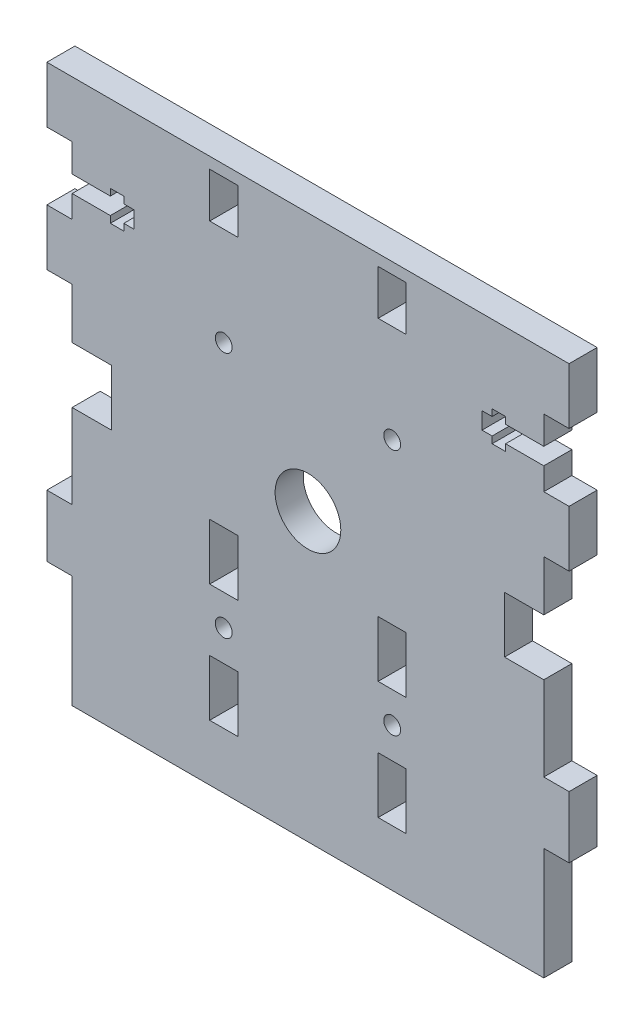
SolidWorks part; units mm, degrees
ref_plane "Plano frontal" through (0, 0, 0) normal (0, 0, 1) x (1, 0, 0)
ref_plane "Plano superior" through (0, 0, 0) normal (0, 1, 0) x (1, 0, 0)
ref_plane "Plano direito" through (0, 0, 0) normal (1, 0, 0) x (0, 0, -1)
sketch "Model" plane through (0, 0, 0) normal (0, 0, 1) x (1, 0, 0)
  line L0 (-56.5, 54) -> (-51.5, 54)
  line L1 (-51.5, 54) -> (-51.5, 64)
  line L2 (-51.5, 64) -> (-56.5, 64)
  line L3 (-56.5, 64) -> (-56.5, 54)
  line L4 (-26.5, 75) -> (-21.5, 75)
  line L5 (-21.5, 75) -> (-21.5, 85)
  line L6 (-21.5, 85) -> (-26.5, 85)
  line L7 (-26.5, 85) -> (-26.5, 75)
  line L8 (-56.5, 131) -> (-51.5, 131)
  line L9 (-51.5, 131) -> (-51.5, 139)
  line L10 (-51.5, 139) -> (-56.5, 139)
  line L11 (-56.5, 139) -> (-56.5, 131)
  line L12 (-26.5, 131) -> (-21.5, 131)
  line L13 (-21.5, 131) -> (-21.5, 139)
  line L14 (-21.5, 139) -> (-26.5, 139)
  line L15 (-26.5, 139) -> (-26.5, 131)
  line L16 (-26.5, 54) -> (-21.5, 54)
  line L17 (-21.5, 54) -> (-21.5, 64)
  line L18 (-21.5, 64) -> (-26.5, 64)
  line L19 (-26.5, 64) -> (-26.5, 54)
  line L20 (-56.5, 75) -> (-51.5, 75)
  line L21 (-51.5, 75) -> (-51.5, 85)
  line L22 (-51.5, 85) -> (-56.5, 85)
  line L23 (-56.5, 85) -> (-56.5, 75)
  line L24 (-85.5, 109) -> (-85.5, 119)
  line L25 (-85.5, 119) -> (-81, 119)
  line L26 (-81, 119) -> (-81, 123)
  line L27 (-81, 123) -> (-74.2, 123)
  line L28 (-74.2, 123) -> (-74.2, 121.8)
  line L29 (-74.2, 121.8) -> (-71.8, 121.8)
  line L30 (-71.8, 121.8) -> (-71.8, 123)
  line L31 (-71.8, 123) -> (-70, 123)
  line L32 (-70, 123) -> (-70, 126)
  line L33 (-70, 126) -> (-71.8, 126)
  line L34 (-71.8, 126) -> (-71.8, 127.2)
  line L35 (-71.8, 127.2) -> (-74.2, 127.2)
  line L36 (-74.2, 127.2) -> (-74.2, 126)
  line L37 (-74.2, 126) -> (-81, 126)
  line L38 (-81, 126) -> (-81, 131)
  line L39 (-81, 131) -> (-85.5, 131)
  line L40 (-85.5, 131) -> (-85.5, 141)
  line L41 (-85.5, 141) -> (7.5, 141)
  line L42 (7.5, 141) -> (7.5, 131)
  line L43 (7.5, 131) -> (3, 131)
  line L44 (3, 131) -> (3, 126)
  line L45 (3, 126) -> (-3.8, 126)
  line L46 (-3.8, 126) -> (-3.8, 127.2)
  line L47 (-3.8, 127.2) -> (-6.2, 127.2)
  line L48 (-6.2, 127.2) -> (-6.2, 126)
  line L49 (-6.2, 126) -> (-8, 126)
  line L50 (-8, 126) -> (-8, 123)
  line L51 (-8, 123) -> (-6.2, 123)
  line L52 (-6.2, 123) -> (-6.2, 121.8)
  line L53 (-6.2, 121.8) -> (-3.8, 121.8)
  line L54 (-3.8, 121.8) -> (-3.8, 123)
  line L55 (-3.8, 123) -> (3, 123)
  line L56 (3, 123) -> (3, 119)
  line L57 (3, 119) -> (7.5, 119)
  line L58 (7.5, 119) -> (7.5, 109)
  line L59 (7.5, 109) -> (3, 109)
  line L60 (3, 109) -> (3, 100)
  line L61 (3, 100) -> (-4, 100)
  line L62 (-4, 100) -> (-4, 90)
  line L63 (-4, 90) -> (3, 90)
  line L64 (3, 90) -> (3, 75)
  line L65 (3, 75) -> (7.5, 75)
  line L66 (7.5, 75) -> (7.5, 64)
  line L67 (7.5, 64) -> (3, 64)
  line L68 (3, 64) -> (3, 63)
  line L69 (3, 63) -> (3, 44)
  line L70 (3, 44) -> (-81, 44)
  line L71 (-81, 44) -> (-81, 63)
  line L72 (-81, 63) -> (-81, 64)
  line L73 (-81, 64) -> (-85.5, 64)
  line L74 (-85.5, 64) -> (-85.5, 75)
  line L75 (-85.5, 75) -> (-81, 75)
  line L76 (-81, 75) -> (-81, 90)
  line L77 (-81, 90) -> (-74, 90)
  line L78 (-74, 90) -> (-74, 100)
  line L79 (-74, 100) -> (-81, 100)
  line L80 (-81, 100) -> (-81, 109)
  line L81 (-81, 109) -> (-85.5, 109)
  circle A0 centre (-24, 113.5) radius 1.5
  circle A1 centre (-24, 69.5) radius 1.5
  circle A2 centre (-54, 113.5) radius 1.5
  circle A3 centre (-54, 69.5) radius 1.5
  circle A4 centre (-39, 95) radius 5.85
extrude "Ressalto-extrusão1" add sketch "Model" along normal blind 5
